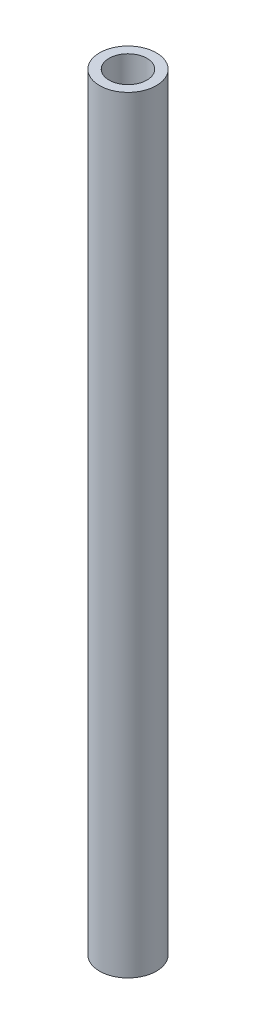
SolidWorks part; units mm, degrees
other "Frame Spacer Tube"
ref_plane "Front Plane" through (0, 0, 0) normal (0, 0, 1) x (1, 0, 0)
ref_plane "Top Plane" through (0, 0, 0) normal (0, 1, 0) x (1, 0, 0)
ref_plane "Right Plane" through (0, 0, 0) normal (1, 0, 0) x (0, 0, -1)
sketch3d "Base Outline Sketch datum points"
  point P0 (0, -150.6, 0)
  point P1 (10, -150.6, 0)
  point P2 (0, -150.6, -10)
ref_plane "Base Outline Sketch plane" through (0, -150.6, 0) normal (0, 1, 0) x (1, 0, 0)
sketch "Base Outline Sketch" plane through (0, -150.6, 0) normal (0, 1, 0) x (1, 0, 0)
  circle A0 centre (-56.2917, -50) radius 3
  circle A1 centre (-56.2917, -50) radius 2
extrude "Base Outline" add sketch "Base Outline Sketch" along normal blind 81 separate body
